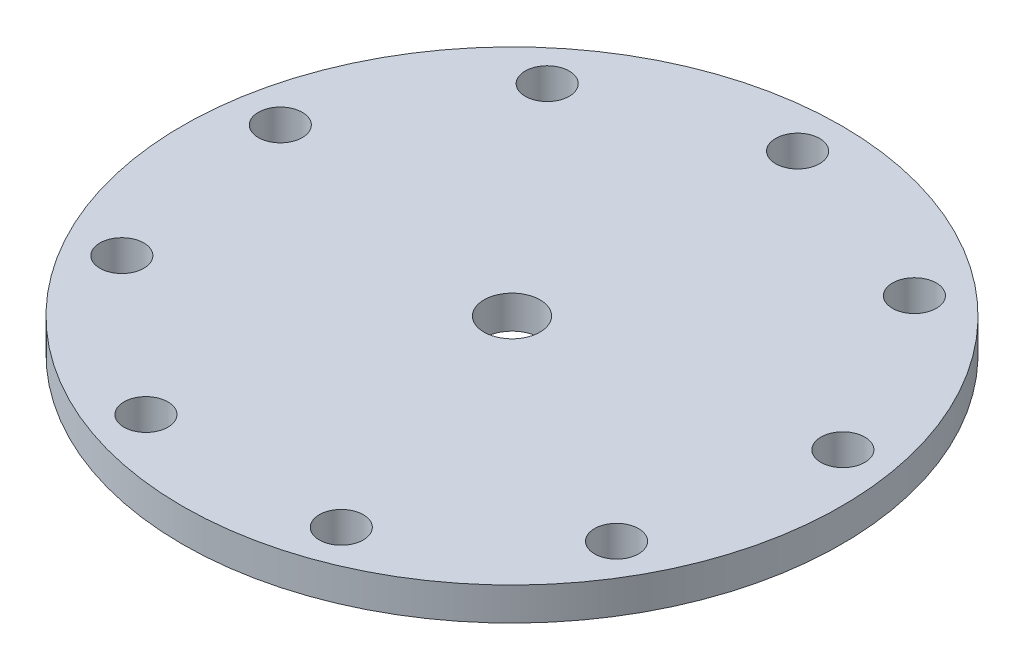
SolidWorks part; units mm, degrees
ref_plane "前视基准面" through (0, 0, 0) normal (0, 0, 1) x (1, 0, 0)
ref_plane "上视基准面" through (0, 0, 0) normal (0, 1, 0) x (1, 0, 0)
ref_plane "右视基准面" through (0, 0, 0) normal (1, 0, 0) x (0, 0, -1)
other "Configuration Table"
sketch "草图1" plane through (0, 0, 0) normal (0, 1, 0) x (1, 0, 0)
  line L0 (0, 52) -> (0, 0) construction
  circle A0 centre (0, 0) radius 60
  circle A1 centre (0, 52) radius 4
  circle A2 centre (33.425, 39.8343) radius 4
  circle A3 centre (51.21, 9.0297) radius 4
  circle A4 centre (45.0333, -26) radius 4
  circle A5 centre (17.785, -48.864) radius 4
  circle A6 centre (-17.785, -48.864) radius 4
  circle A7 centre (-45.0333, -26) radius 4
  circle A8 centre (-51.21, 9.0297) radius 4
  circle A9 centre (-33.425, 39.8343) radius 4
  circle A10 centre (0, 0) radius 5.1
  point P23 (0, 0)
  dimension "D1" = 120
  dimension "D2" = 8
  dimension "D4" = 9
  dimension "D5" = 52
  dimension "D7" = 10.2
  dimension "D3" = 52
  dimension "D6" = 35.5701
extrude "凸台-拉伸1" add sketch "草图1" along normal blind 6 contours A0
